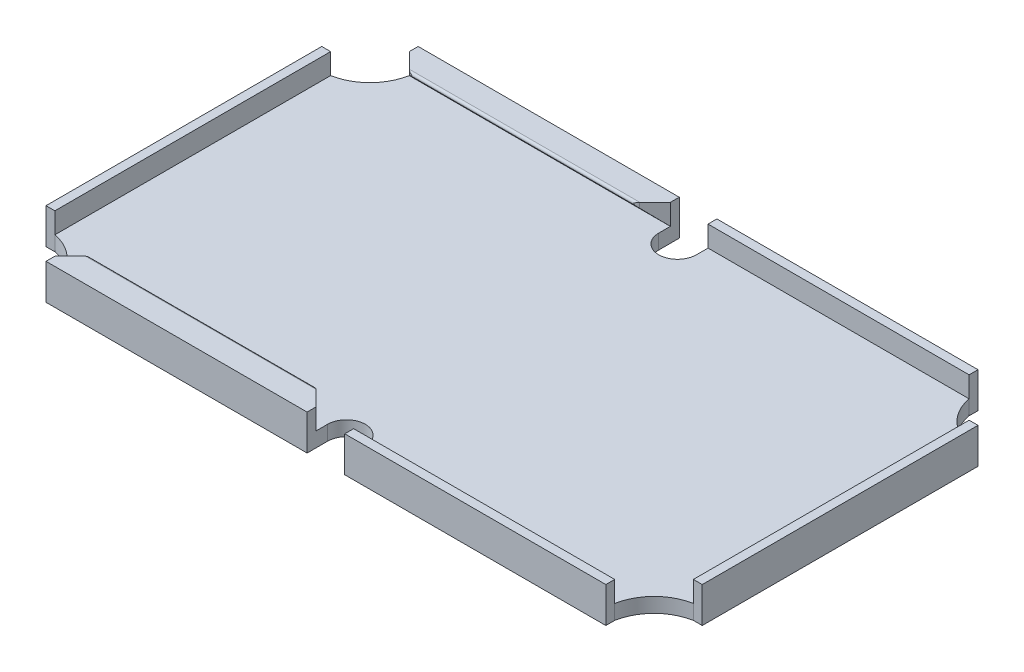
SolidWorks part; units mm, degrees
ref_plane "Alzado" through (0, 0, 0) normal (0, 0, 1) x (1, 0, 0)
ref_plane "Planta" through (0, 0, 0) normal (0, 1, 0) x (1, 0, 0)
ref_plane "Vista lateral" through (0, 0, 0) normal (1, 0, 0) x (0, 0, -1)
sketch "Croquis1" plane through (0, 0, 0) normal (0, 1, 0) x (1, 0, 0)
  line L1 (-46.2, 26.2) -> (46.2, 26.2)
  line L2 (-46.2, 26.2) -> (-46.2, -26.2)
  line L3 (-46.2, -26.2) -> (46.2, -26.2)
  line L4 (46.2, 26.2) -> (46.2, -26.2)
  line L5 (-46.2, 26.2) -> (46.2, -26.2) construction
  line L6 (-46.2, -26.2) -> (46.2, 26.2) construction
  point P0 (0, 0)
  dimension "D1" = 92.4
  dimension "D2" = 52.4
extrude "Saliente-Extruir1" add sketch "Croquis1" along normal blind 5
sketch "Croquis2" plane through (0, 5, 0) normal (0, 1, 0) x (1, 0, 0)
  line L0 (-46.2, 26.2) -> (-46.2, -26.2) construction
  line L1 (44.95, 24.95) -> (-44.95, 24.95)
  line L2 (44.95, 24.95) -> (44.95, -24.95)
  line L3 (44.95, -24.95) -> (-44.95, -24.95)
  line L4 (-44.95, 24.95) -> (-44.95, -24.95)
  line L5 (44.95, 24.95) -> (-44.95, -24.95) construction
  line L6 (44.95, -24.95) -> (-44.95, 24.95) construction
  line L7 (-46.2, -26.2) -> (46.2, -26.2) construction
  point P0 (0, 0)
  dimension "D1" = 1.25
  dimension "D2" = 1.25
extrude "Cortar-Extruir1" cut sketch "Croquis2" against normal blind 2.93
sketch "Croquis3" plane through (0, 2.07, 0) normal (0, 1, 0) x (1, 0, 0)
  line L0 (0, -20.66) -> (0, -26.2) construction
  line L2 (-46.2, -26.2) -> (46.2, -26.2) construction
  line L3 (-44.95, -24.95) -> (44.95, -24.95) construction
  line L4 (2.65, -23.31) -> (-2.65, -23.31) construction
  line L5 (2.65, -23.31) -> (2.65, -26.2)
  line L6 (2.65, -26.2) -> (-2.65, -26.2)
  line L7 (-2.65, -23.31) -> (-2.65, -26.2)
  line L8 (2.65, -23.31) -> (-2.65, -26.2) construction
  line L9 (2.65, -26.2) -> (-2.65, -23.31) construction
  arc A0 (-2.65, -23.31) -> (2.65, -23.31) centre (0, -23.31) cw
  point P3 (0, -24.755)
  dimension "D1" = 5.3
  dimension "D2" = 1.64
extrude "Cortar-Extruir2" cut sketch "Croquis3" against normal up to surface and the other way up to surface
sketch "Croquis4" plane through (0, 2.07, 0) normal (0, 1, 0) x (1, 0, 0)
  line L0 (-46.2, 26.2) -> (-46.2, -26.2) construction
  line L1 (-46.2, -26.2) -> (-2.65, -26.2) construction
  line L2 (-46.2, 26.2) -> (-46.2, -26.2) construction
  line L3 (-46.2, -26.2) -> (-2.65, -26.2) construction
  line L5 (-46.2, -19.4142) -> (-46.2, -26.2)
  line L6 (-46.2, -26.2) -> (-39.4142, -26.2)
  line L7 (-44.95, 24.95) -> (-44.95, -24.95) construction
  line L8 (-44.95, -24.95) -> (-2.65, -24.95) construction
  line L9 (-44.95, 24.95) -> (-44.95, -24.95) construction
  line L10 (-44.95, -24.95) -> (-2.65, -24.95) construction
  line L11 (-39.4142, -24.95) -> (-39.4142, -26.2)
  line L12 (-44.95, -19.4142) -> (-46.2, -19.4142)
  arc A0 (-46.2, -19.3) -> (-39.3, -26.2) centre (-46.2, -26.2) cw construction
  arc A2 (-39.4142, -24.95) -> (-44.95, -19.4142) centre (-46.2, -26.2) ccw
  dimension "D1" = 6.9
extrude "Cortar-Extruir3" cut sketch "Croquis4" against normal up to surface and the other way up to surface
mirror "Simetría1" about plane through (0, 0, 0) normal (1, 0, 0) of "Cortar-Extruir3"
mirror "Simetría2" about plane through (0, 0, 0) normal (0, 0, 1) of "Simetría1", "Cortar-Extruir3"
mirror "Simetría3" about plane through (0, 0, 0) normal (0, 0, 1) of "Cortar-Extruir2"
sketch "Croquis7" plane through (-2.65, 0, 0) normal (1, 0, 0) x (0, 0, -1)
  line L0 (-24.95, 2.07) -> (-24.95, 5)
  line L1 (-24.95, 5) -> (-22.8, 5)
  line L2 (-24.95, 2.07) -> (-22.5854, 4.4904)
  line L3 (-24.95, 4.7) -> (-22.5, 4.7) construction
  arc A0 (-22.8, 5) -> (-22.5854, 4.4904) centre (-22.8, 4.7) cw
  dimension "D2" = 0.3
  dimension "D1" = 2.45
extrude "Saliente-Extruir3" add sketch "Croquis7" against normal up to surface (42.0642 mm away)
sketch "Croquis8" plane through (0, 2.07, 0) normal (0, 1, 0) x (1, 0, 0)
  line L0 (-39.4142, -24.95) -> (-37.2571, -22.7929)
  line L1 (-36.55, -22.5) -> (-5.5142, -22.5)
  line L2 (-4.8071, -22.7929) -> (-2.65, -24.95)
  line L3 (-39.4142, -24.95) -> (-40.7358, -24.95)
  line L4 (-40.7358, -24.95) -> (-40.7358, -18.2276)
  line L5 (-40.7358, -18.2276) -> (-1.6835, -18.2276)
  line L6 (-1.6835, -18.2276) -> (-1.6835, -24.95)
  line L7 (-1.6835, -24.95) -> (-2.65, -24.95)
  line L8 (-2.65, -22.5) -> (-39.4142, -22.5) construction
  line L9 (-2.65, -22.5) -> (-39.4142, -22.5) construction
  arc A0 (-4.8071, -22.7929) -> (-5.5142, -22.5) centre (-5.5142, -23.5) ccw
  arc A1 (-36.55, -22.5) -> (-37.2571, -22.7929) centre (-36.55, -23.5) ccw
  dimension "D3" = 1
  dimension "D1" = 45
  dimension "D2" = 45
extrude "Cortar-Extruir5" cut sketch "Croquis8" along normal up to surface (2.93 mm away) up to face at (21.0321, 5, 25.575)
mirror "Simetría4" about plane through (0, 0, 0) normal (0, 0, 1) of "Cortar-Extruir5", "Saliente-Extruir3"
